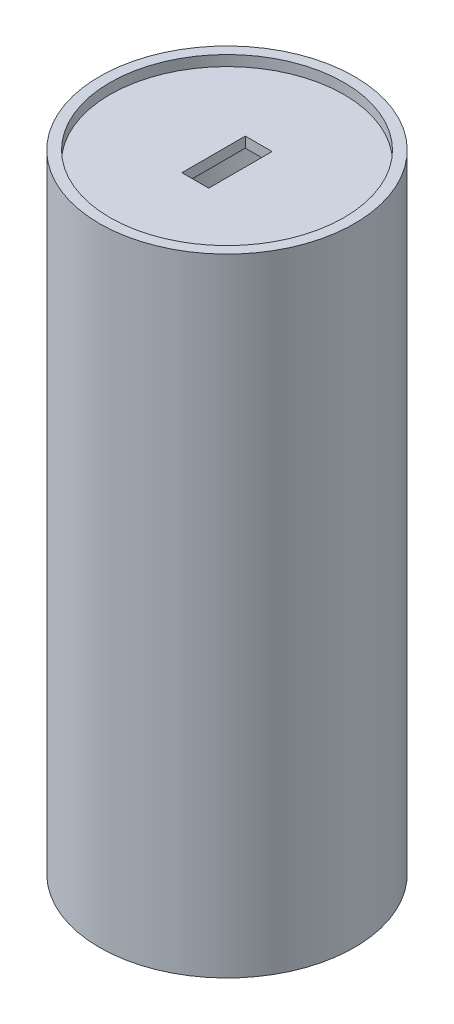
SolidWorks part; units mm, degrees
ref_plane "Front Plane" through (0, 0, 0) normal (0, 0, 1) x (1, 0, 0)
ref_plane "Top Plane" through (0, 0, 0) normal (0, 1, 0) x (1, 0, 0)
ref_plane "Right Plane" through (0, 0, 0) normal (1, 0, 0) x (0, 0, -1)
sketch "Sketch1" plane through (0, 0, 0) normal (0, 1, 0) x (1, 0, 0)
  circle A0 centre (0, 0) radius 61
  circle A1 centre (0, 0) radius 56
extrude "Boss-Extrude1" add sketch "Sketch1" along normal blind 300 contours A0 A1
ref_plane "Plane1" through (0, 20, 0) normal (0, 1, 0) x (1, 0, 0)
sketch "Sketch3" plane through (0, 20, 0) normal (0, 1, 0) x (1, 0, 0)
  circle A0 centre (0, 0) radius 56
extrude "Boss-Extrude2" add sketch "Sketch3" along normal blind 5
sketch "Sketch4" plane through (0, 20, 0) normal (0, -1, 0) x (1, 0, 0)
  circle A4 centre (10, 0) radius 1.5
  circle A5 centre (0, 10) radius 1.5
  circle A6 centre (-10, 0) radius 1.5
  circle A7 centre (0, -10) radius 1.5
  point P0 (0, 0)
  dimension "D1" = 10
  dimension "D2" = 3
  dimension "D3" = 3
  dimension "D4" = 3
  dimension "D5" = 3
  dimension "D6" = 20
  dimension "D7" = 10
  dimension "D8" = 10
extrude "Cut-Extrude1" cut sketch "Sketch4" against normal up to next
ref_plane "Plane2" through (0, 290, 0) normal (0, 1, 0) x (1, 0, 0)
sketch "Sketch5" plane through (0, 290, 0) normal (0, 1, 0) x (1, 0, 0)
  circle A0 centre (0, 0) radius 56
extrude "Boss-Extrude3" add sketch "Sketch5" along normal blind 5
sketch "Sketch6" plane through (0, 295, 0) normal (0, 1, 0) x (1, 0, 0)
  line L1 (-6.41, 15.17) -> (6.41, 15.17)
  line L2 (-6.41, 15.17) -> (-6.41, -15.17)
  line L3 (-6.41, -15.17) -> (6.41, -15.17)
  line L4 (6.41, 15.17) -> (6.41, -15.17)
  line L5 (-6.41, 15.17) -> (6.41, -15.17) construction
  line L6 (-6.41, -15.17) -> (6.41, 15.17) construction
  point P0 (0, 0)
  dimension "D1" = 12.82
  dimension "D2" = 30.34
extrude "Cut-Extrude2" cut sketch "Sketch6" against normal up to next
